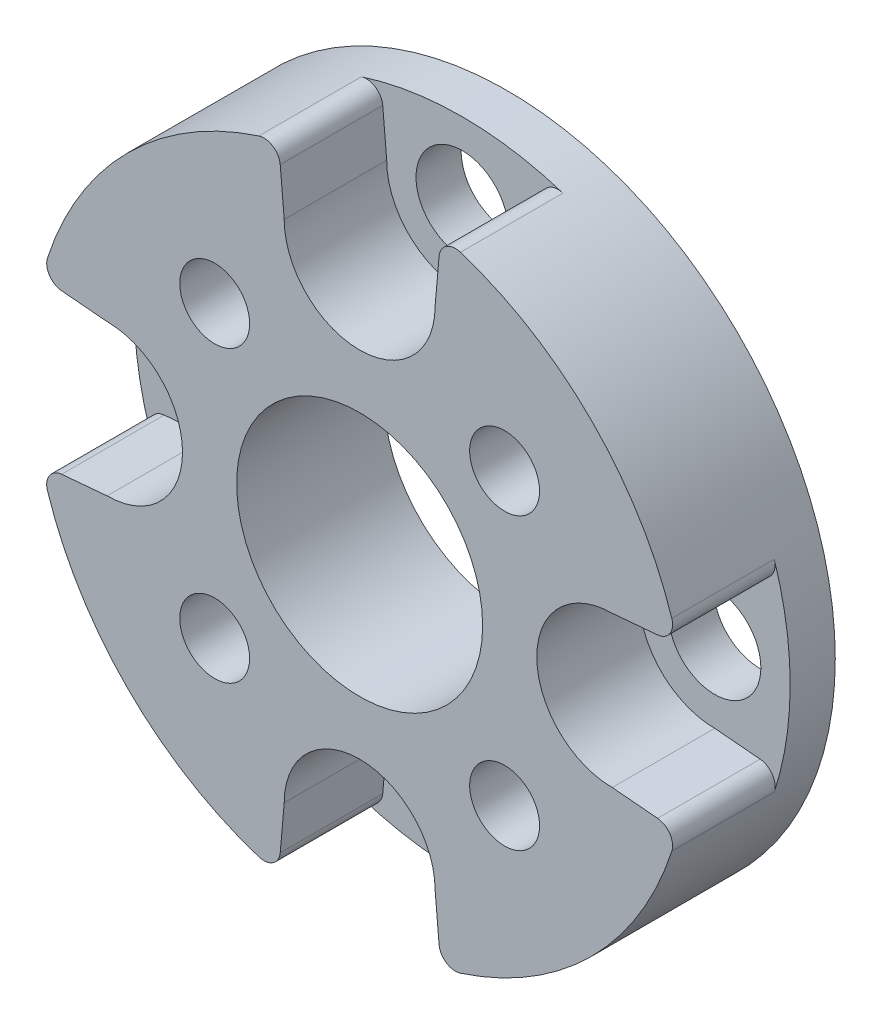
SolidWorks part; units mm, degrees
material "6061 Alloy"
ref_plane "Front Plane" through (0, 0, 0) normal (0, 0, 1) x (1, 0, 0)
ref_plane "Top Plane" through (0, 0, 0) normal (0, 1, 0) x (1, 0, 0)
ref_plane "Right Plane" through (0, 0, 0) normal (1, 0, 0) x (0, 0, -1)
sketch "Sketch1" plane through (0, 0, 0) normal (0, 0, 1) x (1, 0, 0)
  circle A0 centre (0, 0) radius 12.7
  circle A1 centre (0, 0) radius 4.7625
  dimension "D1" = 25.4
  dimension "D2" = 9.525
extrude "Boss-Extrude1" add sketch "Sketch1" along normal mid plane 5.715
hole_wizard "#6-32 Tapped Hole1" positions "Sketch4" profile "Sketch3" tap size "#6-32" standard "Ansi Inch" end condition up to next
sketch "Sketch4" plane through (0, 0, 2.8575) normal (0, 0, 1) x (1, 0, 0)
  line L0 (0, 0) -> (5.6127, 5.6127) construction
  line L2 (0, 0) -> (9.779, 0) construction
  point P0 (5.6127, 5.6127)
  point P19 (5.6127, -5.6127)
  point P20 (-5.6127, -5.6127)
  point P21 (-5.6127, 5.6127)
  dimension "D1" = 7.9375
  dimension "D2" = 45
  dimension "D3" = 9.779
  dimension "D4" = 4
sketch "Sketch3" plane through (5.6127, 5.6127, 2.8575) normal (1, 0, 0) x (0, -1, 0)
  line L0 (0, 0) -> (0, 5.715)
  line L1 (0, 5.715) -> (1.3525, 5.715)
  line L2 (1.3525, 5.715) -> (1.3525, 0)
  line L5 (1.3525, 0) -> (0, 0)
  line L11 (0, -6.35) -> (0, 107.95) construction
  dimension "Thru Tap Drill Dia." = 2.7051
  dimension "Thru Tap Drill Depth" = 5.715
cosmetic thread "Hole Thread1" parameters "D2"=3.5052
cosmetic thread "Hole Thread2" parameters "D2"=3.5052
cosmetic thread "Hole Thread3" parameters "D2"=3.5052
cosmetic thread "Hole Thread4" parameters "D2"=3.5052
sketch "Sketch5" plane through (0, 0, 2.8575) normal (0, 0, 1) x (1, 0, 0)
  line L0 (0, 0) -> (9.779, 0) construction
  line L1 (9.779, 2.921) -> (12.3052, 3.142)
  line L2 (9.779, -2.921) -> (12.3052, -3.142)
  line L3 (2.921, -9.779) -> (3.142, -12.3052)
  line L4 (-2.921, -9.779) -> (-3.142, -12.3052)
  line L5 (-9.779, -2.921) -> (-12.3052, -3.142)
  line L6 (-9.779, 2.921) -> (-12.3052, 3.142)
  line L7 (-2.921, 9.779) -> (-3.142, 12.3052)
  line L8 (2.921, 9.779) -> (3.142, 12.3052)
  arc A0 (9.779, 2.921) -> (9.779, -2.921) centre (9.779, 0) ccw
  circle A1 centre (0, 0) radius 12.7 construction
  arc A2 (12.3052, -3.142) -> (12.3052, 3.142) centre (0, 0) ccw
  arc A3 (2.921, -9.779) -> (-2.921, -9.779) centre (0, -9.779) ccw
  arc A4 (-3.142, -12.3052) -> (3.142, -12.3052) centre (0, 0) ccw
  arc A5 (-9.779, -2.921) -> (-9.779, 2.921) centre (-9.779, 0) ccw
  arc A6 (-12.3052, 3.142) -> (-12.3052, -3.142) centre (0, 0) ccw
  arc A7 (-2.921, 9.779) -> (2.921, 9.779) centre (0, 9.779) ccw
  arc A8 (3.142, 12.3052) -> (-3.142, 12.3052) centre (0, 0) ccw
  dimension "D1" = 9.779
  dimension "D3" = 5.842
  dimension "D4" = 5
  dimension "D2" = 4
extrude "Cut-Extrude1" cut sketch "Sketch5" against normal blind 3.9688
hole_wizard "9/64 (0.14063) Diameter Hole1" positions "Sketch9" profile "Sketch8" hole size "9/64" standard "Ansi Inch" end condition up to next
sketch "Sketch9" plane through (0, 0, -1.1113) normal (0, 0, 1) x (1, 0, 0)
  point P0 (0, 9.779)
  point P1 (-9.779, 0)
  point P4 (0, -9.779)
  point P7 (9.779, 0)
sketch "Sketch8" plane through (0, 9.779, -1.1113) normal (1, 0, 0) x (0, -1, 0)
  line L0 (0, 0) -> (0, 1.7462)
  line L1 (0, 1.7462) -> (1.786, 1.7462)
  line L2 (1.786, 1.7462) -> (1.786, 0)
  line L5 (1.786, 0) -> (0, 0)
  line L11 (0, -6.35) -> (0, 107.95) construction
  dimension "Thru Hole Dia." = 3.572
  dimension "Thru Hole Depth" = 1.7462
fillet "Fillet1" radius 0.635 8 edges at (12.3052, -3.142, 0.8731) (12.3052, 3.142, 0.8731) (3.142, -12.3052, 0.8731) (-3.142, -12.3052, 0.8731) (-12.3052, 3.142, 0.8731) (-12.3052, -3.142, 0.8731) (3.142, 12.3052, 0.8731) (-3.142, 12.3052, 0.8731)
